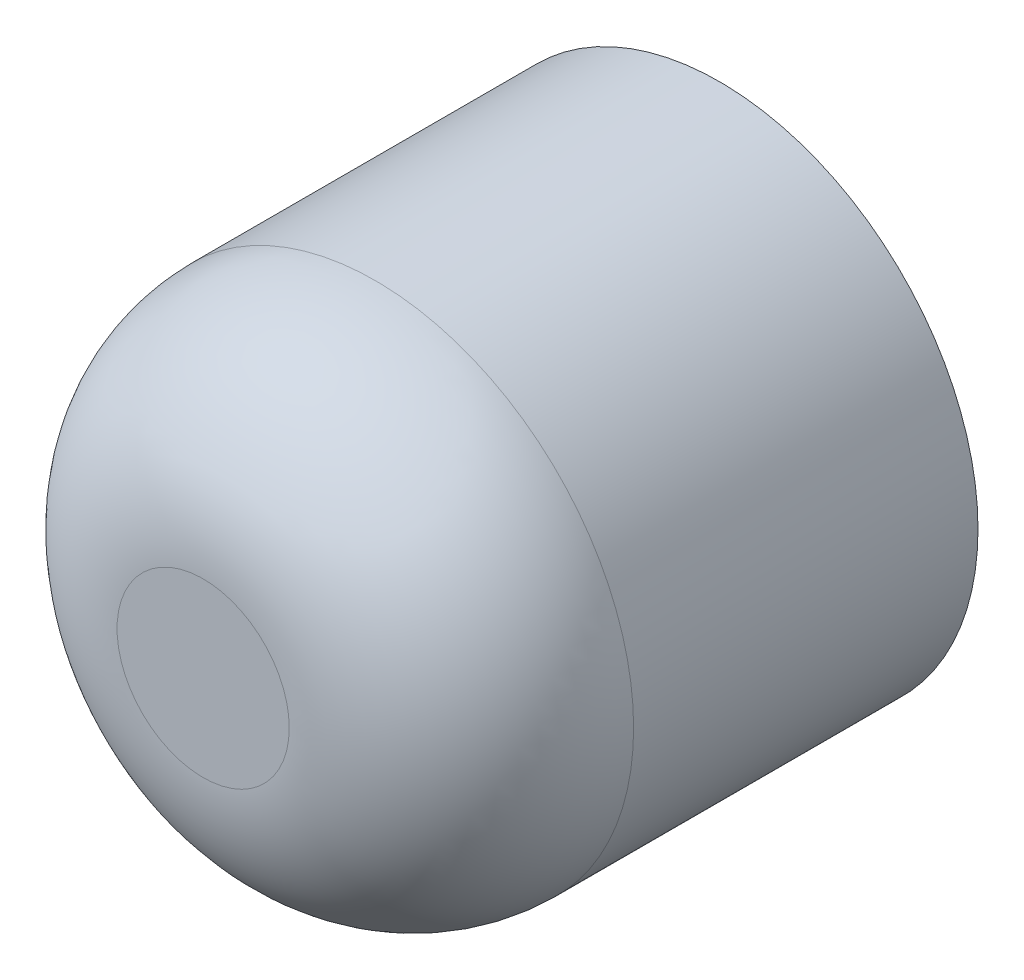
SolidWorks part; units mm, degrees
ref_plane "前视基准面" through (0, 0, 0) normal (0, 0, 1) x (1, 0, 0)
ref_plane "上视基准面" through (0, 0, 0) normal (0, 1, 0) x (1, 0, 0)
ref_plane "右视基准面" through (0, 0, 0) normal (1, 0, 0) x (0, 0, -1)
sketch "草图1" plane through (0, 0, 0) normal (0, 0, 1) x (1, 0, 0)
  circle A0 centre (0, 0) radius 1.5
extrude "凸台-拉伸1" add sketch "草图1" along normal blind 3
fillet "圆角1" radius 1 1 edges at (1.5, 0, 3)
sketch "草图2" plane through (0, 0, 0) normal (0, 0, -1) x (-1, 0, 0)
  line L1 (0.866, 0) -> (0.433, 0.75)
  line L2 (0.433, 0.75) -> (-0.433, 0.75)
  line L3 (-0.433, 0.75) -> (-0.866, 0)
  line L4 (-0.866, 0) -> (-0.433, -0.75)
  line L5 (-0.433, -0.75) -> (0.433, -0.75)
  line L6 (0.433, -0.75) -> (0.866, 0)
  circle A0 centre (0, 0) radius 0.75 construction
extrude "切除-拉伸1" cut sketch "草图2" against normal blind 1.5
